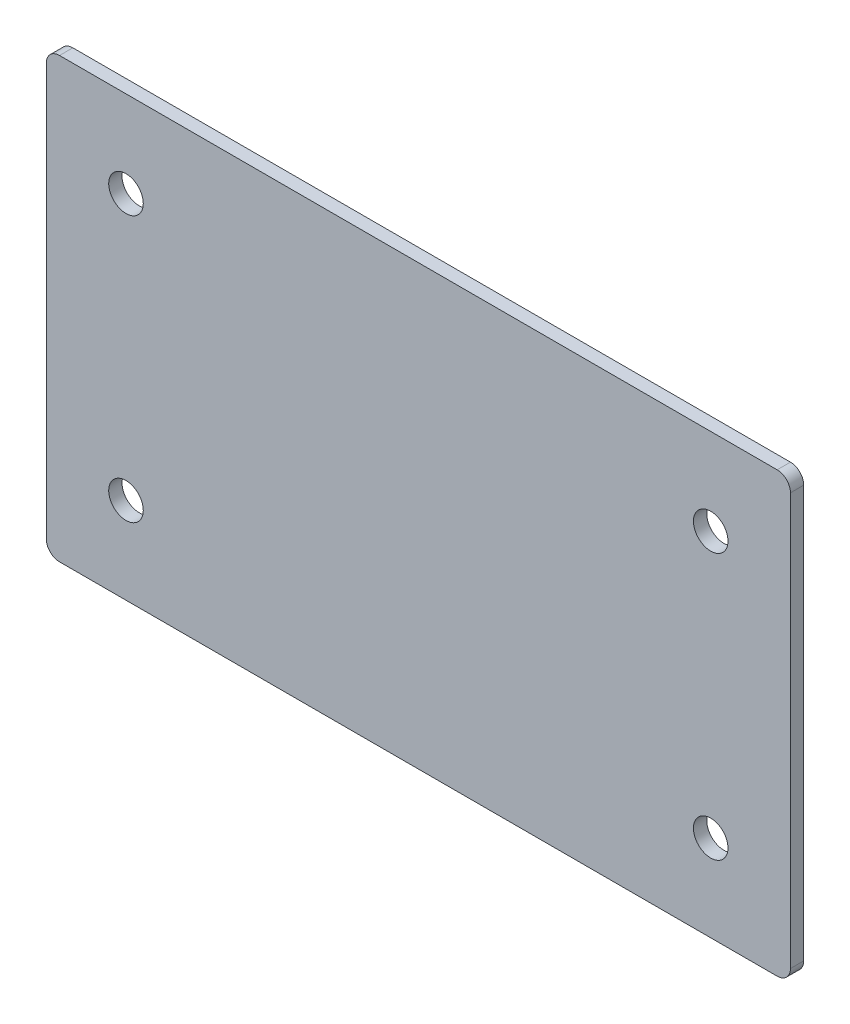
SolidWorks part; units mm, degrees
material "Q355"
ref_plane "前视基准面" through (0, 0, 0) normal (0, 0, 1) x (1, 0, 0)
ref_plane "上视基准面" through (0, 0, 0) normal (0, 1, 0) x (1, 0, 0)
ref_plane "右视基准面" through (0, 0, 0) normal (1, 0, 0) x (0, 0, -1)
sketch "草图1" plane through (0, 0, 0) normal (0, 0, 1) x (1, 0, 0)
  line L1 (-140, 82.5) -> (140, 82.5)
  line L2 (-140, 82.5) -> (-140, -82.5)
  line L3 (-140, -82.5) -> (140, -82.5)
  line L4 (140, 82.5) -> (140, -82.5)
  line L5 (-140, 82.5) -> (140, -82.5) construction
  line L6 (-140, -82.5) -> (140, 82.5) construction
  point P0 (0, 0)
  dimension "D1" = 165
  dimension "D2" = 280
extrude "凸台-拉伸1" add sketch "草图1" along normal blind 5
sketch "草图2" plane through (0, 0, 5) normal (0, 0, 1) x (1, 0, 0)
  line L1 (-110, 50) -> (110, 50) construction
  line L2 (-110, 50) -> (-110, -50) construction
  line L3 (-110, -50) -> (110, -50) construction
  line L4 (110, 50) -> (110, -50) construction
  line L5 (-110, 50) -> (110, -50) construction
  line L6 (-110, -50) -> (110, 50) construction
  circle A0 centre (-110, 50) radius 6.5
  circle A1 centre (110, 50) radius 6.5
  circle A2 centre (-110, -50) radius 6.5
  circle A3 centre (110, -50) radius 6.5
  point P0 (0, 0)
  dimension "D3" = 13
  dimension "D4" = 13
  dimension "D5" = 13
  dimension "D6" = 13
  dimension "D1" = 220
  dimension "D2" = 100
extrude "切除-拉伸1" cut sketch "草图2" against normal blind 6
fillet "圆角1" radius 5 4 edges at (-140, -82.5, 2.5) (140, -82.5, 2.5) (140, 82.5, 2.5) (-140, 82.5, 2.5)
